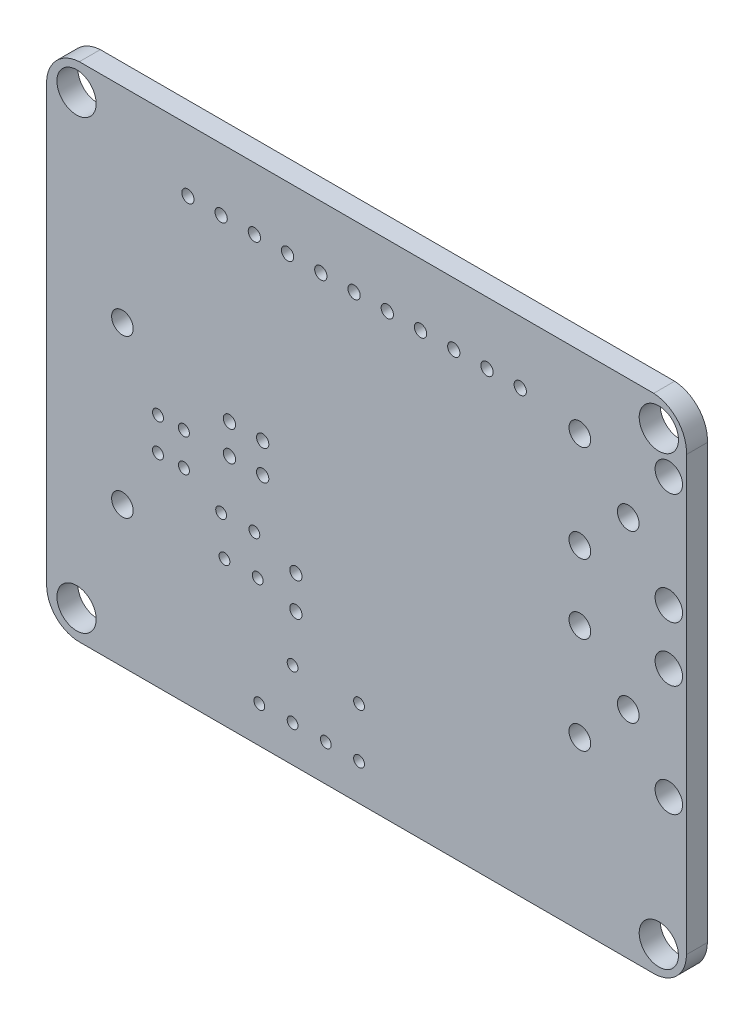
SolidWorks part; units mm, degrees
ref_plane "Front Plane" through (0, 0, 0) normal (0, 0, 1) x (1, 0, 0)
ref_plane "Top Plane" through (0, 0, 0) normal (0, 1, 0) x (1, 0, 0)
ref_plane "Right Plane" through (0, 0, 0) normal (1, 0, 0) x (0, 0, -1)
sketch "17" plane through (0, 0, 0) normal (0, 0, 1) x (1, 0, 0)
  circle A0 centre (19.939, 11.049) radius 0.4127
  circle A1 centre (19.939, 11.049) radius 0.4127
  circle A2 centre (17.399, 11.049) radius 0.4127
  circle A3 centre (17.399, 11.049) radius 0.4127
  circle A4 centre (25.146, 2.794) radius 0.4127
  circle A5 centre (25.146, 2.794) radius 0.4127
  circle A6 centre (27.686, 2.794) radius 0.4127
  circle A7 centre (27.686, 2.794) radius 0.4127
  circle A8 centre (20.066, 2.794) radius 0.4127
  circle A9 centre (20.066, 2.794) radius 0.4127
  circle A10 centre (22.606, 2.794) radius 0.4127
  circle A11 centre (22.606, 2.794) radius 0.4127
  circle A12 centre (17.145, 13.97) radius 0.4127
  circle A13 centre (17.145, 13.97) radius 0.4127
  circle A14 centre (19.685, 13.97) radius 0.4127
  circle A15 centre (19.685, 13.97) radius 0.4127
  circle A16 centre (30.997, 15.5939) radius 0.2159
  circle A17 centre (30.997, 15.5939) radius 0.2159
  circle A18 centre (32.7931, 17.39) radius 0.2159
  circle A19 centre (32.7931, 17.39) radius 0.2159
  circle A20 centre (29.201, 17.39) radius 0.2159
  circle A21 centre (29.201, 17.39) radius 0.2159
  circle A22 centre (30.997, 19.186) radius 0.2159
  circle A23 centre (30.997, 19.186) radius 0.2159
  circle A24 centre (27.4049, 19.186) radius 0.2159
  circle A25 centre (27.4049, 19.186) radius 0.2159
  circle A26 centre (29.201, 20.9821) radius 0.2159
  circle A27 centre (29.201, 20.9821) radius 0.2159
  circle A28 centre (12.319, 18.014) radius 0.4191
  circle A29 centre (12.319, 18.014) radius 0.4191
  circle A30 centre (14.3002, 18.014) radius 0.4191
  circle A31 centre (14.3002, 18.014) radius 0.4191
  circle A32 centre (12.319, 15.514) radius 0.4191
  circle A33 centre (12.319, 15.514) radius 0.4191
  circle A34 centre (9.6012, 10.7442) radius 0.8255
  circle A35 centre (9.6012, 10.7442) radius 0.8255
  circle A36 centre (9.6012, 22.7838) radius 0.8255
  circle A37 centre (9.6012, 22.7838) radius 0.8255
  circle A38 centre (14.3002, 15.514) radius 0.4191
  circle A39 centre (14.3002, 15.514) radius 0.4191
  circle A40 centre (44.56, 12.81) radius 0.829
  circle A41 centre (44.56, 12.81) radius 0.829
  circle A42 centre (48.26, 16.51) radius 0.829
  circle A43 centre (48.26, 16.51) radius 0.829
  circle A44 centre (44.56, 20.21) radius 0.829
  circle A45 centre (44.56, 20.21) radius 0.829
  circle A46 centre (44.56, 25.51) radius 0.829
  circle A47 centre (44.56, 25.51) radius 0.829
  circle A48 centre (48.26, 29.21) radius 0.829
  circle A49 centre (48.26, 29.21) radius 0.829
  circle A50 centre (44.56, 32.91) radius 0.829
  circle A51 centre (44.56, 32.91) radius 0.829
  circle A52 centre (17.78, 20.32) radius 0.4699
  circle A53 centre (17.78, 20.32) radius 0.4699
  circle A54 centre (20.32, 20.32) radius 0.4699
  circle A55 centre (20.32, 20.32) radius 0.4699
  circle A56 centre (17.78, 18.034) radius 0.4699
  circle A57 centre (17.78, 18.034) radius 0.4699
  circle A58 centre (20.32, 18.034) radius 0.4699
  circle A59 centre (20.32, 18.034) radius 0.4699
  circle A60 centre (22.86, 10.287) radius 0.4699
  circle A61 centre (22.86, 10.287) radius 0.4699
  circle A62 centre (22.86, 12.827) radius 0.4699
  circle A63 centre (22.86, 12.827) radius 0.4699
  circle A64 centre (14.605, 33.655) radius 0.4699
  circle A65 centre (14.605, 33.655) radius 0.4699
  circle A66 centre (17.145, 33.655) radius 0.4699
  circle A67 centre (17.145, 33.655) radius 0.4699
  circle A68 centre (19.685, 33.655) radius 0.4699
  circle A69 centre (19.685, 33.655) radius 0.4699
  circle A70 centre (22.225, 33.655) radius 0.4699
  circle A71 centre (22.225, 33.655) radius 0.4699
  circle A72 centre (24.765, 33.655) radius 0.4699
  circle A73 centre (24.765, 33.655) radius 0.4699
  circle A74 centre (27.305, 33.655) radius 0.4699
  circle A75 centre (27.305, 33.655) radius 0.4699
  circle A76 centre (29.845, 33.655) radius 0.4699
  circle A77 centre (29.845, 33.655) radius 0.4699
  circle A78 centre (32.385, 33.655) radius 0.4699
  circle A79 centre (32.385, 33.655) radius 0.4699
  circle A80 centre (34.925, 33.655) radius 0.4699
  circle A81 centre (34.925, 33.655) radius 0.4699
  circle A82 centre (37.465, 33.655) radius 0.4699
  circle A83 centre (37.465, 33.655) radius 0.4699
  circle A84 centre (40.005, 33.655) radius 0.4699
  circle A85 centre (40.005, 33.655) radius 0.4699
  circle A86 centre (41.148, 7.62) radius 0.4699
  circle A87 centre (41.148, 7.62) radius 0.4699
  circle A88 centre (36.068, 7.62) radius 0.4699
  circle A89 centre (36.068, 7.62) radius 0.4699
  circle A90 centre (38.608, 7.874) radius 0.4699
  circle A91 centre (38.608, 7.874) radius 0.4699
  circle A92 centre (22.606, 6.604) radius 0.4127
  circle A93 centre (22.606, 6.604) radius 0.4127
  circle A94 centre (27.686, 6.604) radius 0.4127
  circle A95 centre (27.686, 6.604) radius 0.4127
sketch "20" plane through (0, 0, 0) normal (0, 0, 1) x (1, 0, 0)
  line L0 (50.205, 38.4048) -> (6.31, 38.4048)
  line L1 (3.81, 35.6) -> (3.81, 2.5)
  line L2 (52.705, 35.6) -> (52.705, 2.5)
  line L3 (50.205, 0) -> (6.31, 0)
  arc A0 (6.31, 38.4048) -> (3.81, 35.6) centre (6.4624, 35.7524) ccw
  arc A1 (52.705, 35.6) -> (50.205, 38.4048) centre (50.0526, 35.7524) ccw
  arc A2 (50.205, 0) -> (52.705, 2.5) centre (50.205, 2.5) ccw
  arc A3 (3.81, 2.5) -> (6.31, 0) centre (6.31, 2.5) ccw
  circle A4 centre (6.096, 2.1336) radius 1.5
  circle A5 centre (50.5968, 2.1336) radius 1.5
  circle A6 centre (50.5968, 36.2712) radius 1.5
  circle A7 centre (6.096, 36.2712) radius 1.5
  circle A8 centre (51.36, 12.26) radius 1.05
  circle A9 centre (51.36, 20.76) radius 1.05
  circle A10 centre (51.36, 24.96) radius 1.05
  circle A11 centre (51.36, 33.46) radius 1.05
sketch "51" plane through (0, 0, 0) normal (0, 0, 1) x (1, 0, 0)
  line L0 (-0.181, 22.764) -> (3.719, 22.764)
  line L1 (3.719, 22.764) -> (3.719, 10.764)
  line L2 (3.719, 10.764) -> (-0.181, 10.764)
  line L3 (-0.181, 10.764) -> (-0.181, 22.764)
  arc A0 (3.719, 22.7132) -> (3.719, 22.8148) centre (3.719, 22.764) ccw
  arc A1 (-0.181, 22.8148) -> (-0.181, 22.7132) centre (-0.181, 22.764) ccw
  arc A2 (3.6682, 10.764) -> (3.7698, 10.764) centre (3.719, 10.764) ccw
  arc A3 (3.7698, 22.764) -> (3.6682, 22.764) centre (3.719, 22.764) ccw
  arc A4 (-0.181, 10.8148) -> (-0.181, 10.7132) centre (-0.181, 10.764) ccw
  arc A5 (3.719, 10.7132) -> (3.719, 10.8148) centre (3.719, 10.764) ccw
  arc A6 (-0.1302, 22.764) -> (-0.2318, 22.764) centre (-0.181, 22.764) ccw
  arc A7 (-0.2318, 10.764) -> (-0.1302, 10.764) centre (-0.181, 10.764) ccw
extrude "Boss-Extrude1" add sketch "20" against normal blind 1.6
extrude "Cut-Extrude1" cut sketch "17" against normal blind 1.6 contours A36 | A28 | A30 | A34 | A8 | A10 | A4 | A6 | A92 | A94 | A12 | A32 | A38 | A64 | A66 | A68 | A70 | A72 | A74 | A76 | A78 | A80 | A82 | A84 | A50 | A48 | A46 | A44 | A42 | A40 | A52 | A56 | A54 | A58 | A2 | A14 | A0 | A62 | A60
